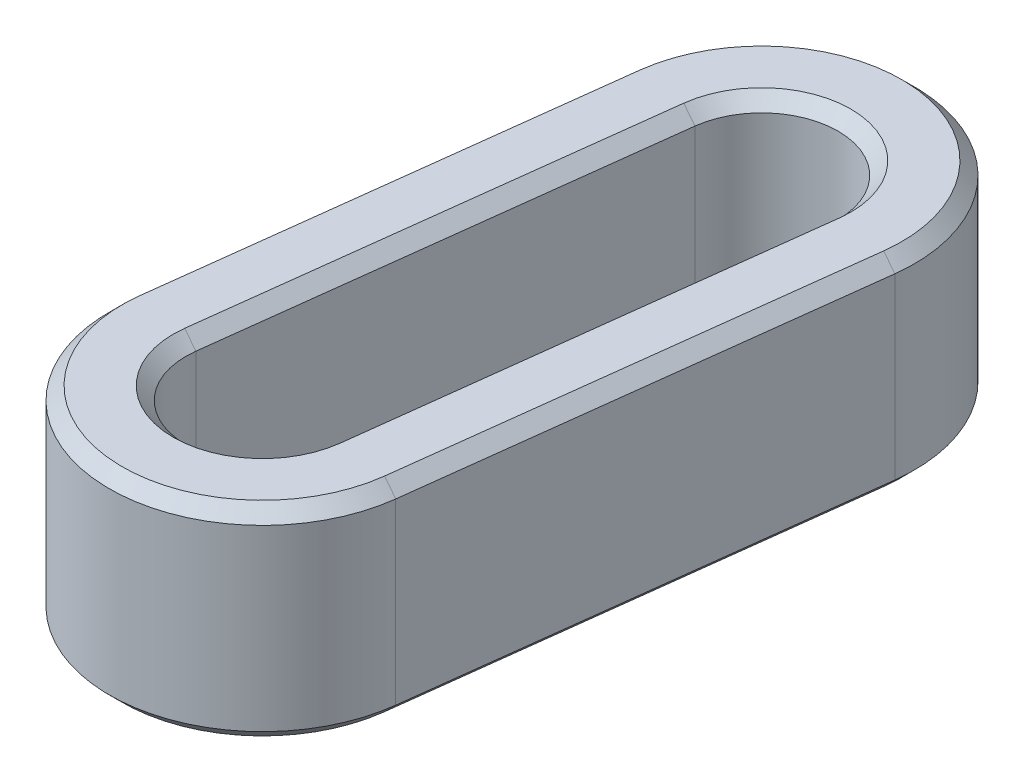
SolidWorks part; units mm, degrees
ref_plane "Front Plane" through (0, 0, 0) normal (0, 0, 1) x (1, 0, 0)
ref_plane "Top Plane" through (0, 0, 0) normal (0, 1, 0) x (1, 0, 0)
ref_plane "Right Plane" through (0, 0, 0) normal (1, 0, 0) x (0, 0, -1)
sketch "Sketch1" plane through (0, 0, 0) normal (0, 1, 0) x (1, 0, 0)
  line L0 (-29.4224, -80.3931) -> (-27.2833, -62.9713)
  line L1 (-26.4448, -80.7587) -> (-24.3057, -63.3369)
  line L2 (-18.3504, -64.0681) -> (-20.4895, -81.4899)
  line L3 (-15.3728, -64.4337) -> (-17.5119, -81.8555)
  arc A0 (-26.4448, -80.7587) -> (-20.4895, -81.4899) centre (-23.4672, -81.1243) ccw
  arc A1 (-18.3504, -64.0681) -> (-24.3057, -63.3369) centre (-21.328, -63.7025) ccw
  arc A2 (-15.3728, -64.4337) -> (-27.2833, -62.9713) centre (-21.328, -63.7025) ccw
  arc A3 (-29.4224, -80.3931) -> (-17.5119, -81.8555) centre (-23.4672, -81.1243) ccw
  dimension "D1" = 3
extrude "Boss-Extrude1" add sketch "Sketch1" along normal blind 8
chamfer "Chamfer1" distance 0.5 angle 45 16 edges at (-19.42, 0, 72.779) (-23.8328, 0, 84.102) (-25.3752, 0, 72.0478) (-20.9624, 0, 60.7248) (-16.4423, 0, 73.1446) (-20.5968, 0, 57.7472) (-28.3529, 0, 71.6822) (-24.1984, 0, 87.0796) (-23.8328, 8, 84.102) (-19.42, 8, 72.779) (-20.9624, 8, 60.7248) (-25.3752, 8, 72.0478) (-28.3529, 8, 71.6822) (-20.5968, 8, 57.7472) (-16.4423, 8, 73.1446) (-24.1984, 8, 87.0796)
